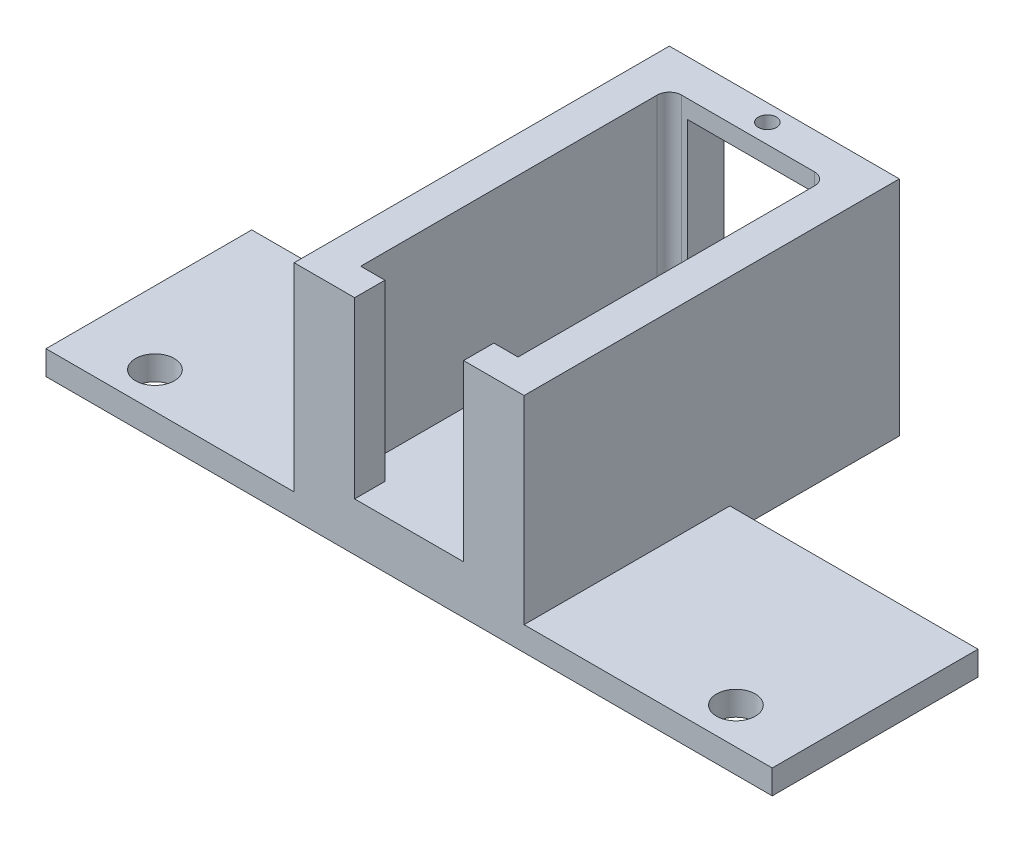
SolidWorks part; units mm, degrees
ref_plane "Front Plane" through (0, 0, 0) normal (0, 0, 1) x (1, 0, 0)
ref_plane "Top Plane" through (0, 0, 0) normal (0, 1, 0) x (1, 0, 0)
ref_plane "Right Plane" through (0, 0, 0) normal (1, 0, 0) x (0, 0, -1)
sketch "Sketch1" plane through (0, 0, 0) normal (0, 1, 0) x (1, 0, 0)
  line L1 (-30, -8.5) -> (30, -8.5)
  line L2 (-30, -8.5) -> (-30, 8.5)
  line L3 (-30, 8.5) -> (30, 8.5)
  line L4 (30, -8.5) -> (30, 8.5)
  line L5 (-30, -8.5) -> (30, 8.5) construction
  line L6 (-30, 8.5) -> (30, -8.5) construction
  point P0 (0, 0)
  dimension "D1" = 60
  dimension "D2" = 17
extrude "Boss-Extrude1" add sketch "Sketch1" along normal blind 4
sketch "Sketch4" plane through (0, 0, -8.5) normal (0, 0, -1) x (-1, 0, 0)
  line L0 (-30, 4) -> (30, 4) construction
  line L1 (9.5, 4) -> (-9.5, 4)
  line L2 (9.5, 4) -> (9.5, 0)
  line L3 (9.5, 0) -> (-9.5, 0)
  line L4 (-9.5, 4) -> (-9.5, 0)
  line L5 (-30, 0) -> (30, 0) construction
  line L6 (0, 2.2) -> (0, -2.2) construction
  dimension "D1" = 19
  dimension "D2" = 9.5
extrude "Boss-Extrude2" add sketch "Sketch4" along normal blind 14
sketch "Sketch5" plane through (0, 4, 0) normal (0, 1, 0) x (1, 0, 0)
  line L0 (-30, -8.5) -> (30, -8.5) construction
  line L1 (-9.5, 22.5) -> (-6.5, 22.5)
  line L2 (-9.5, 22.5) -> (-9.5, -8.5)
  line L3 (-9.5, -8.5) -> (-6.5, -8.5)
  line L4 (-6.5, 22.5) -> (-6.5, -8.5)
  dimension "D1" = 3
extrude "Boss-Extrude3" add sketch "Sketch5" along normal blind 14.4
mirror "Mirror1" about plane through (0, 0, 0) normal (1, 0, 0) of "Boss-Extrude3"
sketch "Sketch6" plane through (0, 4, 0) normal (0, 1, 0) x (1, 0, 0)
  line L0 (6.5, -8.5) -> (6.5, 22.5) construction
  line L1 (-6.5, -8.5) -> (6.5, -8.5)
  line L2 (-6.5, -8.5) -> (-6.5, -6)
  line L3 (-6.5, -6) -> (6.5, -6)
  line L4 (6.5, -8.5) -> (6.5, -6)
  dimension "D1" = 2.5
extrude "Boss-Extrude4" add sketch "Sketch6" along normal up to vertex (14.4 mm away)
sketch "Sketch7" plane through (0, 18.4, 0) normal (0, 1, 0) x (1, 0, 0)
  line L0 (6.5, -6) -> (-6.5, -6) construction
  line L1 (-4.5, -6) -> (4.5, -6)
  line L2 (-4.5, -6) -> (-4.5, -8.5)
  line L3 (-4.5, -8.5) -> (4.5, -8.5)
  line L4 (4.5, -6) -> (4.5, -8.5)
  line L5 (-9.5, -8.5) -> (9.5, -8.5) construction
  line L6 (0, -2.2) -> (0, 2.2) construction
  dimension "D1" = 9
  dimension "D2" = 4.5
extrude "Cut-Extrude1" cut sketch "Sketch7" against normal up to vertex (14.4 mm away)
sketch "Sketch8" plane through (0, 4, 0) normal (0, 1, 0) x (1, 0, 0)
  line L0 (6.5, -6) -> (6.5, 22.5) construction
  line L1 (-6.5, 22.5) -> (6.5, 22.5)
  line L2 (-6.5, 22.5) -> (-6.5, 19.5)
  line L3 (-6.5, 19.5) -> (6.5, 19.5)
  line L4 (6.5, 22.5) -> (6.5, 19.5)
  dimension "D1" = 3
extrude "Boss-Extrude5" add sketch "Sketch8" along normal up to vertex (14.4 mm away)
sketch "Sketch9" plane through (0, 18.4, 0) normal (0, 1, 0) x (1, 0, 0)
  line L0 (0, -2.2) -> (0, 2.2) construction
  line L1 (-6.5, 19.5) -> (6.5, 19.5) construction
  circle A0 centre (0, 21.1) radius 0.75
  dimension "D1" = 1.5
  dimension "D2" = 1.6
extrude "Cut-Extrude2" cut sketch "Sketch9" against normal blind 6
sketch "Sketch10" plane through (0, 0, -22.5) normal (0, 0, -1) x (-1, 0, 0)
  line L0 (0, 2.2) -> (0, -2.2) construction
  line L1 (-5, 16.9) -> (5, 16.9)
  line L2 (-5, 16.9) -> (-5, 8.9)
  line L3 (-5, 8.9) -> (5, 8.9)
  line L4 (5, 16.9) -> (5, 8.9)
  line L5 (-5, 16.9) -> (5, 8.9) construction
  line L6 (-5, 8.9) -> (5, 16.9) construction
  line L7 (-9.5, 18.4) -> (9.5, 18.4) construction
  point P0 (0, 12.9)
  dimension "D1" = 10
  dimension "D2" = 1.5
  dimension "D3" = 8
extrude "Cut-Extrude3" cut sketch "Sketch10" against normal up to vertex (3 mm away)
fillet "Fillet1" radius 1 2 edges at (-6.5, 11.2, -19.5) (6.5, 11.2, -19.5)
sketch "Sketch11" plane through (0, 4, 0) normal (0, 1, 0) x (1, 0, 0)
  line L0 (-30, 8.5) -> (-30, -8.5) construction
  line L1 (-30, -8.5) -> (-9.5, -8.5) construction
  line L2 (30, -8.5) -> (30, 8.5) construction
  circle A0 centre (-24, -5.5) radius 1.6
  circle A1 centre (24, -5.5) radius 1.6
  dimension "D1" = 3.2
  dimension "D2" = 6
  dimension "D3" = 6
  dimension "D4" = 3
extrude "Cut-Extrude4" cut sketch "Sketch11" against normal up to vertex (4 mm away)
sketch "Sketch12" plane through (0, 4, 0) normal (0, 1, 0) x (1, 0, 0)
  line L1 (-30, 8.5) -> (-9.5, 8.5)
  line L2 (-30, 8.5) -> (-30, -8.5)
  line L3 (-30, -8.5) -> (-9.5, -8.5)
  line L4 (-9.5, 8.5) -> (-9.5, -8.5)
extrude "Cut-Extrude5" cut sketch "Sketch12" against normal blind 2
mirror "Mirror2" about plane through (0, 0, 0) normal (1, 0, 0) of "Cut-Extrude5"
sketch "Sketch13" plane through (0, 8.9, 0) normal (0, 1, 0) x (1, 0, 0)
  line L1 (5, 22.5) -> (-5, 22.5)
  line L2 (5, 22.5) -> (5, 19.5)
  line L3 (5, 19.5) -> (-5, 19.5)
  line L4 (-5, 22.5) -> (-5, 19.5)
extrude "Cut-Extrude6" cut sketch "Sketch13" against normal blind 5
